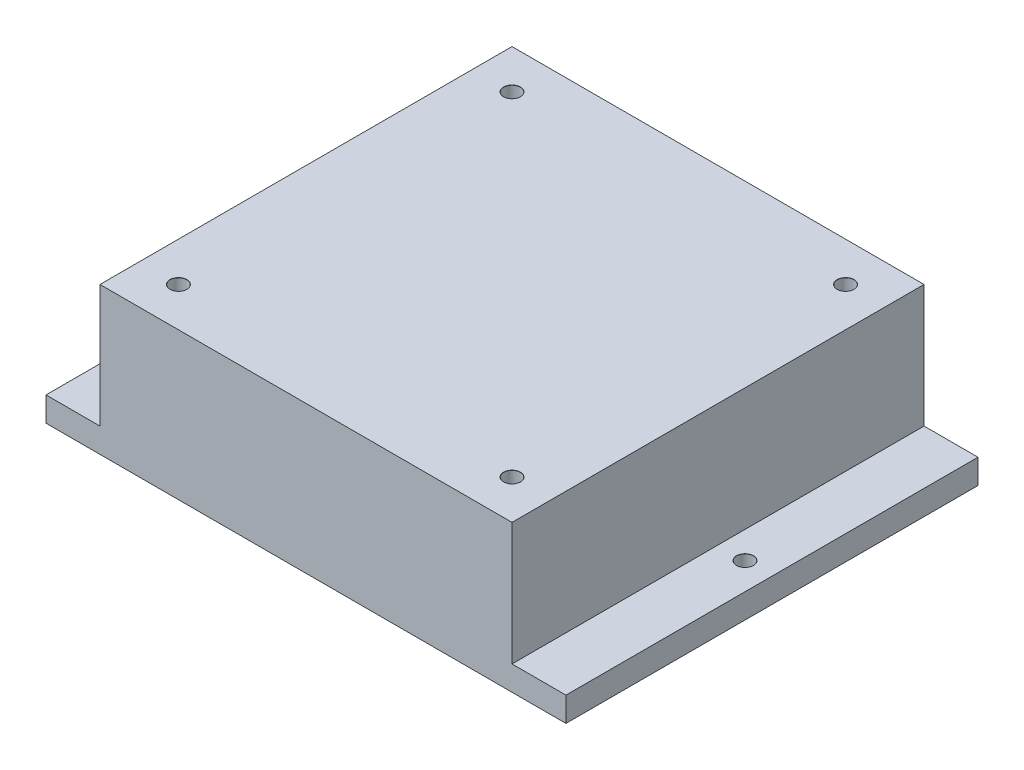
SolidWorks part; units mm, degrees
ref_plane "Front Plane" through (0, 0, 0) normal (0, 0, 1) x (1, 0, 0)
ref_plane "Top Plane" through (0, 0, 0) normal (0, 1, 0) x (1, 0, 0)
ref_plane "Right Plane" through (0, 0, 0) normal (1, 0, 0) x (0, 0, -1)
sketch "Sketch1" plane through (0, 0, 0) normal (0, 1, 0) x (1, 0, 0)
  line L1 (-53, 42) -> (53, 42)
  line L2 (-53, 42) -> (-53, -42)
  line L3 (-53, -42) -> (53, -42)
  line L4 (53, 42) -> (53, -42)
  line L5 (-53, 42) -> (53, -42) construction
  line L6 (-53, -42) -> (53, 42) construction
  point P0 (0, 0)
  dimension "D1" = 106
  dimension "D2" = 84
extrude "Boss-Extrude1" add sketch "Sketch1" along normal blind 30
sketch "Sketch2" plane through (0, 0, 42) normal (0, 0, 1) x (1, 0, 0)
  line L0 (0, -16.5) -> (0, 16.5) construction
  line L1 (53, 30) -> (42, 30)
  line L2 (53, 30) -> (53, 5)
  line L3 (53, 5) -> (42, 5)
  line L4 (42, 30) -> (42, 5)
  line L5 (-42, 30) -> (-42, 5)
  line L6 (-53, 5) -> (-42, 5)
  line L7 (-53, 30) -> (-53, 5)
  line L8 (-53, 30) -> (-42, 30)
  dimension "D1" = 25
  dimension "D2" = 11
extrude "Cut-Extrude1" cut sketch "Sketch2" against normal through all
sketch "Sketch10" plane through (0, 30, 0) normal (0, 1, 0) x (1, 0, 0)
  line L0 (-42, 42) -> (-34, 42) construction
  line L1 (42, 42) -> (-42, 42) construction
  line L2 (-34, 42) -> (-34, 34) construction
  line L3 (42, 34) -> (34, 34) construction
  line L4 (34, -42) -> (34, -34) construction
  line L5 (-42, -34) -> (-34, -34) construction
  point P15 (0, 0)
  dimension "D1" = 8
  dimension "D2" = 8
  dimension "D3" = 4
hole_wizard "M3 Clearance Hole1" positions "Sketch13" profile "Sketch14" hole size "M3" standard "ISO"
sketch "Sketch13" plane through (0, 30, 0) normal (0, 1, 0) x (1, 0, 0)
  point P0 (-34, 34)
  point P3 (34, 34)
  point P6 (34, -34)
  point P9 (-34, -34)
sketch "Sketch14" plane through (-34, 30, -34) normal (1, 0, 0) x (0, 0, 1)
  line L0 (0, 0) -> (0, 11.0215)
  line L1 (0, 11.0215) -> (1.7, 10)
  line L2 (1.7, 10) -> (1.7, 0.025)
  line L3 (1.7, 0.025) -> (1.725, 0)
  line L5 (1.725, 0) -> (0, 0)
  line L6 (-1.7, 0.025) -> (-1.725, 0) construction
  line L10 (0, 11.0215) -> (-1.7, 10) construction
  line L11 (0, -6.35) -> (0, 107.95) construction
  dimension "Hole Dia." = 3.4
  dimension "Hole Depth" = 10
  dimension "Near C'Sink Dia." = 3.45
  dimension "Near C'Sink Angle" = 90
  dimension "Drill Angle" = 118
sketch "Sketch15" plane through (0, 5, 0) normal (0, 1, 0) x (1, 0, 0)
  line L0 (47.5, 42) -> (47.5, 0) construction
  line L1 (42, 42) -> (53, 42) construction
  line L2 (-47.5, 42) -> (-47.5, 0) construction
  line L3 (-53, 42) -> (-42, 42) construction
hole_wizard "M3 Clearance Hole2" positions "Sketch16" profile "Sketch17" hole size "M3" standard "ISO" end condition through all
sketch "Sketch16" plane through (0, 5, 0) normal (0, 1, 0) x (1, 0, 0)
  point P0 (-47.5, 0)
  point P3 (47.5, 0)
sketch "Sketch17" plane through (-47.5, 5, 0) normal (1, 0, 0) x (0, 0, 1)
  line L0 (0, 0) -> (0, 5)
  line L1 (0, 5) -> (1.7, 5)
  line L2 (1.7, 5) -> (1.7, 0.025)
  line L3 (1.7, 0.025) -> (1.725, 0)
  line L5 (1.725, 0) -> (0, 0)
  line L6 (-1.7, 0.025) -> (-1.725, 0) construction
  line L11 (0, -6.35) -> (0, 107.95) construction
  dimension "Thru Hole Dia." = 3.4
  dimension "Thru Hole Depth" = 5
  dimension "Near C'Sink Dia." = 3.45
  dimension "Near C'Sink Angle" = 90
